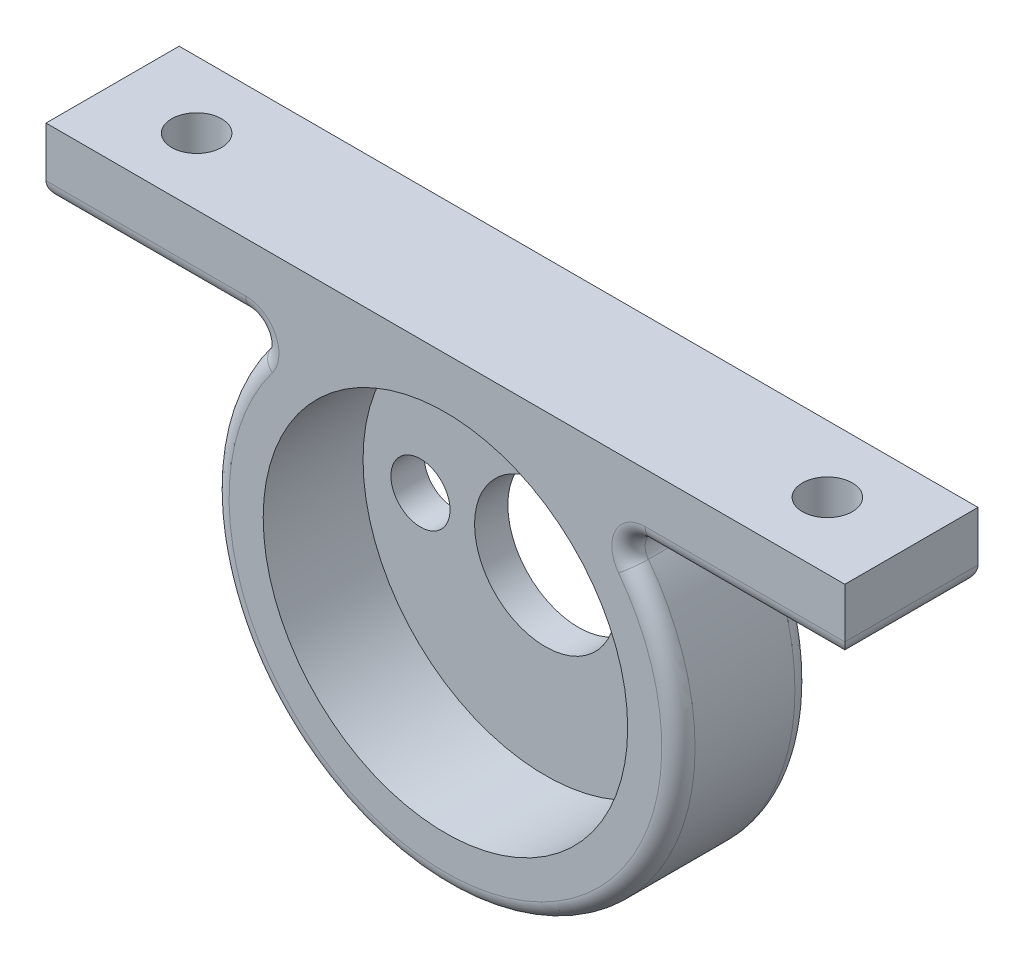
SolidWorks part; units mm, degrees
ref_plane "Alzado" through (0, 0, 0) normal (0, 0, 1) x (1, 0, 0)
ref_plane "Planta" through (0, 0, 0) normal (0, 1, 0) x (1, 0, 0)
ref_plane "Vista lateral" through (0, 0, 0) normal (1, 0, 0) x (0, 0, -1)
sketch "Croquis1" plane through (0, 0, 0) normal (0, 0, 1) x (1, 0, 0)
  line L0 (0, 14) -> (24, 14)
  line L1 (0, 14) -> (-24, 14)
  line L2 (-24, 14) -> (-24, 10)
  line L3 (-24, 10) -> (-9.798, 10)
  line L4 (24, 14) -> (24, 10)
  line L5 (24, 10) -> (9.798, 10)
  arc A1 (-9.798, 10) -> (9.798, 10) centre (0, 0) ccw
  dimension "D1" = 14
  dimension "D2" = 14
  dimension "D3" = 48
  dimension "D5" = 4
  dimension "D6" = 4
  dimension "D7" = 24
extrude "Saliente-Extruir1" add sketch "Croquis1" along normal blind 8
fillet "Redondeo1" radius 1 10 edges at (-16.899, 10, 8) (-16.899, 10, 0) (16.899, 10, 8) (16.899, 10, 0) (-9.798, 10, 4) (0, -14, 8) (9.798, 10, 4) (0, -14, 0) (24, 10, 4) (-24, 10, 4)
sketch "Croquis2" plane through (0, 10, 0) normal (0, -1, 0) x (1, 0, 0)
  line L0 (23, 1) -> (23, 7) construction
  line L2 (12, 1) -> (23, 1) construction
  line L4 (-23, 1) -> (-12, 1) construction
  line L5 (-23, 7) -> (-23, 1) construction
  circle A0 centre (-18.9495, 4) radius 1.5
  circle A1 centre (18.9495, 4) radius 1.5
  dimension "D1" = 3
  dimension "D2" = 3
  dimension "D3" = 4.0505
  dimension "D4" = 3
  dimension "D5" = 3
  dimension "D6" = 4.0505
extrude "Cortar-Extruir1" cut sketch "Croquis2" against normal through all
sketch "Croquis3" plane through (0, 0, 8) normal (0, 0, 1) x (1, 0, 0)
  circle A0 centre (0, 0) radius 10.95
  dimension "D1" = 21.9
extrude "Cortar-Extruir2" cut sketch "Croquis3" against normal blind 6
sketch "Croquis4" plane through (0, 0, 0) normal (0, 0, -1) x (-1, 0, 0)
  line L0 (-24, 14) -> (24, 14) construction
  circle A0 centre (0, 0) radius 4.25
  circle A1 centre (7.5, 0) radius 1.775
  circle A2 centre (-7.5, 0) radius 1.775
  dimension "D1" = 8.5
  dimension "D2" = 7.5
  dimension "D3" = 7.5
  dimension "D4" = 3.55
  dimension "D5" = 3.55
  dimension "D6" = 14
  dimension "D7" = 14
extrude "Cortar-Extruir3" cut sketch "Croquis4" against normal through all
